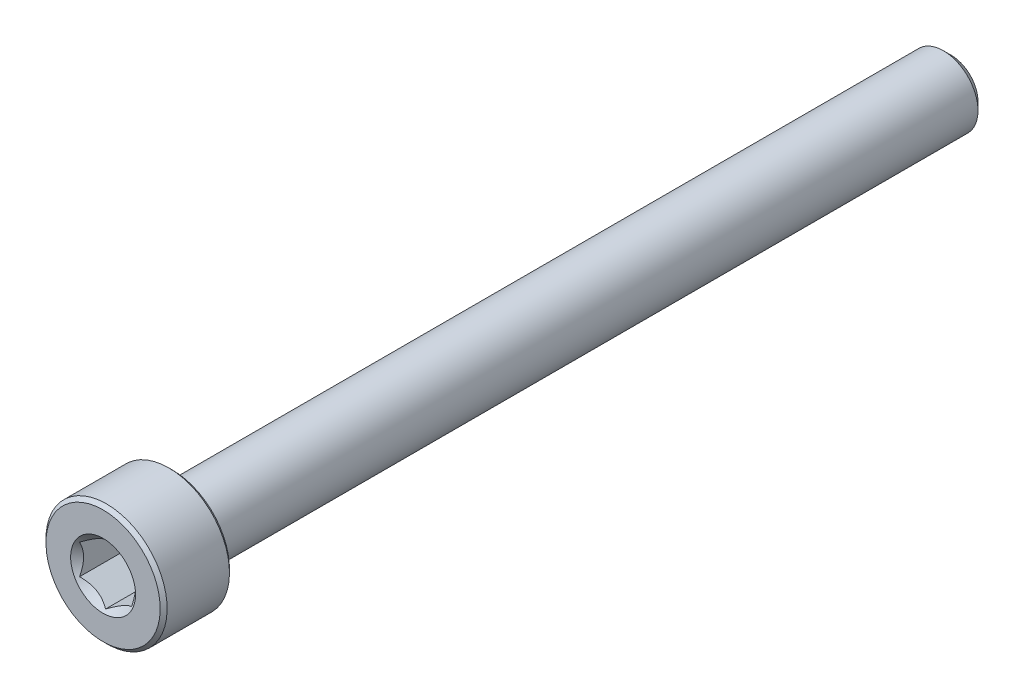
SolidWorks part; units mm, degrees
ref_plane "Front Plane" through (0, 0, 0) normal (0, 0, 1) x (1, 0, 0)
ref_plane "Top Plane" through (0, 0, 0) normal (0, 1, 0) x (1, 0, 0)
ref_plane "Right Plane" through (0, 0, 0) normal (1, 0, 0) x (0, 0, -1)
sketch "Sketch1" plane through (0, 0, 0) normal (1, 0, 0) x (0, 0, -1)
  line L0 (-24.5, 0) -> (24.5, 0) construction
  line L1 (24.5, 0) -> (24.5, 1.5453) construction
  line L2 (24.5, 1.5453) -> (24.0453, 2) construction
  line L3 (24.0453, 2) -> (23.975, 2) construction
  line L4 (23.975, 2) -> (-20.5, 2) construction
  line L5 (-20.5, 2) -> (-20.5, 3.5) construction
  line L6 (-20.5, 3.5) -> (-24.5, 3.5) construction
  line L7 (-24.5, 3.5) -> (-24.5, 0) construction
  line L8 (24.5, 1.5453) -> (24.5, 2) construction
  line L9 (24.4563, 2.0758) -> (24.8063, 1.4696) construction
  line L10 (24.8063, 1.4696) -> (25.1562, 2.0758) construction
  line L11 (25.1562, 2.0758) -> (24.4563, 2.0758) construction
  line L12 (24.8063, 2.0758) -> (24.8063, 2) construction
  line L13 (24.8063, 1.4696) -> (24.8063, 1.5453) construction
  line L14 (24.7625, 1.5453) -> (24.85, 1.5453) construction
  line L15 (24.5, 2) -> (25.1125, 2) construction
  line L16 (24.4781, 2.0379) -> (25.1344, 2.0379) construction
  line L17 (24.5, 0) -> (24.5, -2) construction
  line L18 (-20.7, 3.5) -> (-20.5, 3.3) construction
  line L19 (-24.3, 3.5) -> (-24.5, 3.3) construction
  line L20 (-20.5, 2) -> (-20.5, 0) construction
  line L21 (-20.5, 1) -> (-5.5, 1) construction
  line L22 (-5.5, 1) -> (9.5, 1) construction
  line L23 (9.5, 1) -> (24.5, 1) construction
  line L24 (-5.5, 1) -> (-5.5, 2) construction
  line L25 (-5.5, 2) -> (-5.5, 3.5) construction
  line L26 (9.5, 1) -> (9.5, 3.5) construction
  point P0 (-24.5, 1.5)
  point P3 (22.75, 2)
  point P4 (0, 0)
  point P18 (9.5, 2)
  point P22 (24.8063, 1.5453)
  point P24 (23.975, 2)
  point P25 (24.8063, 2)
  point P28 (24.8063, 2.0379)
  point P29 (22.75, -2)
  point P30 (-5.5, 2)
  point P31 (-22.5, 3.5)
  point P37 (-21.2, 3.5)
  point P38 (-24.2, 3.5)
  point P45 (-5.5, 1)
  point P46 (9.5, 1)
  dimension "D2" = 0.0875
  dimension "D7" = 0.2
  dimension "D8" = 0.2
  dimension "D9" = 0.2
  dimension "D10" = 0.1
  dimension "D11" = 0.5
  dimension "Drive Size" = 3
  dimension "Head Diameter" = 7
  dimension "Head Height" = 4
  dimension "Thread Pitch" = 0.7
  dimension "Thread Size" = 4
  dimension "Length" = 45
  dimension "D12" = 0.525
  dimension "D4" = 1.75
  dimension "D3" = 45
sketch "Sketch2" plane through (0, 0, 0) normal (1, 0, 0) x (0, 0, -1)
  line L0 (-24.5, 0) -> (-24.5, 3.3)
  line L1 (-24.3, 3.5) -> (-20.7, 3.5)
  line L2 (-20.5, 3.3) -> (-20.5, 2.2)
  line L4 (24.0453, 2) -> (24.5, 1.5453)
  line L5 (24.5, 1.5453) -> (24.5, 0)
  line L6 (-20.5, 3.5) -> (-24.5, 3.5) construction
  line L7 (24.5, 0) -> (-24.5, 0)
  line L8 (-24.3, 3.5) -> (-24.5, 3.3) construction
  line L10 (-24.3, 3.5) -> (-24.5, 3.3)
  line L14 (-20.7, 3.5) -> (-20.5, 3.3) construction
  line L16 (-20.7, 3.5) -> (-20.5, 3.3)
  line L17 (-20.5, 2) -> (-20.5, 3.5) construction
  line L19 (-20.3, 2) -> (24.0453, 2)
  line L20 (23.975, 2) -> (-20.5, 2) construction
  arc A1 (-20.5, 2.2) -> (-20.3, 2) centre (-20.3, 2.2) ccw
  dimension "D3" = 0.2
revolve "Revolve1" add sketch "Sketch2" angle 360 about L7
sketch "Sketch3" plane through (0, 0, 24.5) normal (0, 0, 1) x (1, 0, 0)
  line L1 (1.5, -0.866) -> (1.5, 0.866)
  line L2 (1.5, 0.866) -> (0, 1.7321)
  line L3 (0, 1.7321) -> (-1.5, 0.866)
  line L4 (-1.5, 0.866) -> (-1.5, -0.866)
  line L5 (-1.5, -0.866) -> (0, -1.7321)
  line L6 (0, -1.7321) -> (1.5, -0.866)
  circle A0 centre (0, 0) radius 1.5 construction
  circle A1 centre (0, 0) radius 3.5 construction
  circle A2 centre (0, 0) radius 3.5 construction
  circle A3 centre (0, 0) radius 1.7321 construction
  point P13 (0, 0)
extrude "Cut-Extrude1" cut sketch "Sketch3" against normal offset from surface (3 mm away) 1 up to face at (0, 3.3, 20.5)
sketch "Sketch4" plane through (0, 0, 24.5) normal (0, 0, 1) x (1, 0, 0)
  circle A0 centre (0, 0) radius 1.875
  dimension "D1" = 3.75
extrude "Cut-Extrude2" cut sketch "Sketch4" against normal up to vertex (2 mm away) draft 45 up to point (0, 3.5, 22.5)
sketch "Sketch11" plane through (0, 0, 0) normal (1, 0, 0) x (0, 0, -1)
  line L0 (-24.5, 0) -> (24.5, 0) construction
  line L1 (-24.5, 0) -> (24.5, 0) construction
  line L2 (-12.0625, 0) -> (-12.0625, 2) construction
  line L3 (23.975, 2) -> (-20.5, 2) construction
  line L4 (16.0625, 0) -> (16.0625, 2) construction
  line L6 (24.5, 1.5453) -> (24.5, 2) construction
  point P2 (-12.0625, 0)
  point P3 (16.0625, 0)
  dimension "D1" = 8.4375
  dimension "D2" = 8.4375
sketch "Sketch8" [suppressed] plane through (0, 0, 0) normal (1, 0, 0) x (0, 0, -1)
  line L0 (-3, 0) -> (-3, 2)
  line L1 (-2.8, -2) -> (-2.8, 2) construction
  line L2 (-3, 2) -> (-2.8, 2)
  line L4 (-2.8, 2) -> (-1.6453, 0)
  line L5 (-1.6453, 0) -> (-3, 0)
  line L6 (6.475, 2) -> (-3, 2) construction
  line L7 (-7, 0) -> (7, 0) construction
  dimension "D1" = 60
equation "\"D2@Sketch1\" = \"Thread Pitch@Sketch1\" / 8"
equation "\"D7@Sketch1\" = \"Head Height@Sketch1\" * .05"
equation "\"D8@Sketch1\"=\"D7@Sketch1\""
equation "\"D9@Sketch1\"=\"D7@Sketch1\""
equation "\"D10@Sketch1\"=\"D7@Sketch1\"/2"
equation "\"D11@Sketch1\"=\"D10@Sketch1\"*5"
equation "\"D4@Sketch1\"=\"Thread Pitch@Sketch1\"*2.5"
equation "\"D12@Sketch1\"=\"Thread Pitch@Sketch1\"*.75"
equation "\"D3@Sketch2\" = \"Thread Size@Sketch1\" * 0.05"
equation "\"D1@Sketch11\"=\"Length@Sketch1\"*0.1875"
equation "\"D2@Sketch11\"=\"D1@Sketch11\""
equation "\"D1@Sketch4\"=\"Drive Size@Sketch1\"*1.25"
